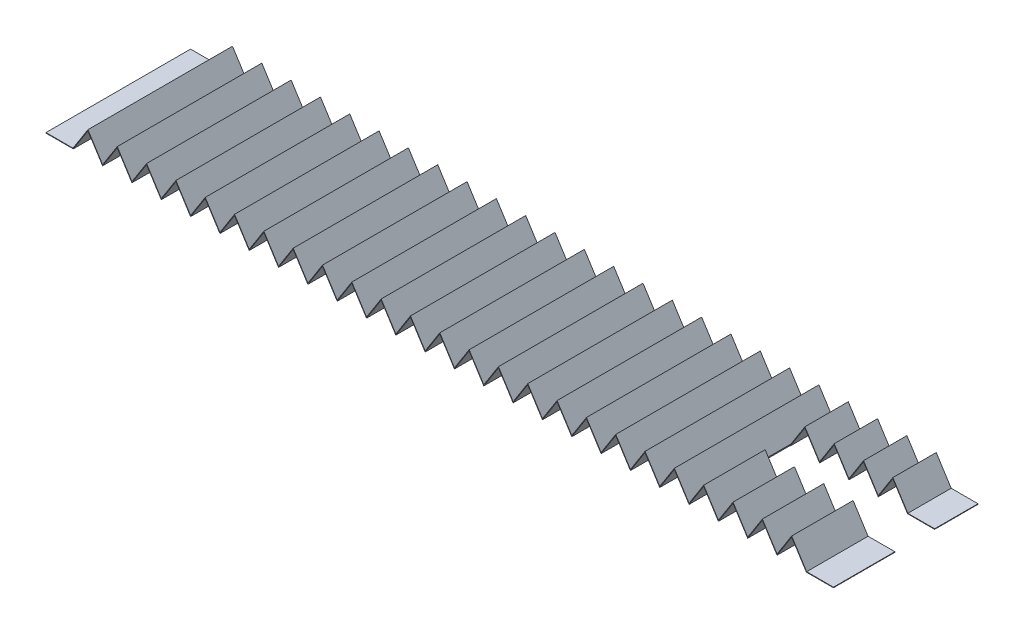
SolidWorks part; units mm, degrees
ref_plane "Front Plane" through (0, 0, 0) normal (0, 0, 1) x (1, 0, 0)
ref_plane "Top Plane" through (0, 0, 0) normal (0, 1, 0) x (1, 0, 0)
ref_plane "Right Plane" through (0, 0, 0) normal (1, 0, 0) x (0, 0, -1)
sketch "Sketch1" plane through (0, 0, 0) normal (0, 0, 1) x (1, 0, 0)
  line L0 (0, 0) -> (8.1143, 12.7345)
  line L1 (8.1143, 12.7345) -> (16.2286, 0)
  line L2 (0, 0) -> (511, 0) construction
  line L3 (16.2286, 0) -> (24.3429, 12.7345)
  line L4 (24.3429, 12.7345) -> (32.4572, 0)
  line L5 (32.4572, 0) -> (40.5715, 12.7345)
  line L6 (40.5715, 12.7345) -> (48.6858, 0)
  line L7 (48.6858, 0) -> (56.8001, 12.7345)
  line L8 (56.8001, 12.7345) -> (64.9144, 0)
  line L9 (64.9144, 0) -> (73.0287, 12.7345)
  line L10 (73.0287, 12.7345) -> (81.143, 0)
  line L11 (81.143, 0) -> (89.2573, 12.7345)
  line L12 (89.2573, 12.7345) -> (97.3716, 0)
  line L13 (97.3716, 0) -> (105.4859, 12.7345)
  line L14 (105.4859, 12.7345) -> (113.6002, 0)
  line L15 (113.6002, 0) -> (121.7145, 12.7345)
  line L16 (121.7145, 12.7345) -> (129.8288, 0)
  line L17 (129.8288, 0) -> (137.9431, 12.7345)
  line L18 (137.9431, 12.7345) -> (146.0574, 0)
  line L19 (0, 0) -> (-15.1, 0)
  line L20 (146.0574, 0) -> (154.1717, 12.7345)
  line L21 (154.1717, 12.7345) -> (162.286, 0)
  line L22 (162.286, 0) -> (170.4003, 12.7345)
  line L23 (170.4003, 12.7345) -> (178.5146, 0)
  line L24 (178.5146, 0) -> (186.6289, 12.7345)
  line L25 (186.6289, 12.7345) -> (194.7432, 0)
  line L26 (194.7432, 0) -> (202.8575, 12.7345)
  line L27 (202.8575, 12.7345) -> (210.9718, 0)
  line L28 (210.9718, 0) -> (219.0861, 12.7345)
  line L29 (219.0861, 12.7345) -> (227.2004, 0)
  line L30 (227.2004, 0) -> (235.3147, 12.7345)
  line L31 (235.3147, 12.7345) -> (243.429, 0)
  line L32 (243.429, 0) -> (251.5433, 12.7345)
  line L33 (251.5433, 12.7345) -> (259.6576, 0)
  line L34 (259.6576, 0) -> (267.7719, 12.7345)
  line L35 (267.7719, 12.7345) -> (275.8862, 0)
  line L36 (275.8862, 0) -> (284.0005, 12.7345)
  line L37 (284.0005, 12.7345) -> (292.1148, 0)
  line L39 (292.1148, 0) -> (300.2291, 12.7345)
  line L40 (300.2291, 12.7345) -> (308.3434, 0)
  line L41 (308.3434, 0) -> (316.4577, 12.7345)
  line L42 (316.4577, 12.7345) -> (324.572, 0)
  line L43 (324.572, 0) -> (332.6863, 12.7345)
  line L44 (332.6863, 12.7345) -> (340.8006, 0)
  line L45 (340.8006, 0) -> (348.9149, 12.7345)
  line L46 (348.9149, 12.7345) -> (357.0292, 0)
  line L47 (357.0292, 0) -> (365.1435, 12.7345)
  line L48 (365.1435, 12.7345) -> (373.2578, 0)
  line L49 (373.2578, 0) -> (381.3721, 12.7345)
  line L50 (340.715, -119) -> (340.715, 187) construction
  line L51 (381.3721, 12.7345) -> (389.4864, 0)
  line L52 (389.4864, 0) -> (397.6007, 12.7345)
  line L53 (397.6007, 12.7345) -> (405.715, 0)
  line L54 (405.715, 0) -> (420.715, 0)
  dimension "D1" = 511
  dimension "D2" = 15.1
  dimension "D3" = 15
  dimension "D4" = 16.2286
  dimension "D6" = 80
  dimension "D5" = 25
extrude "Extrude-Thin1" add sketch "Sketch1" along normal mid plane 80 thin thin type one direction reverse wall 0.3
sketch "Sketch2" plane through (0, 0, 0) normal (0, 1, 0) x (1, 0, 0)
  line L1 (340.715, -6) -> (420.715, -6)
  line L2 (340.715, -6) -> (340.715, 16)
  line L3 (340.715, 16) -> (420.715, 16)
  line L4 (420.715, -6) -> (420.715, 16)
  line L5 (340.715, -6) -> (420.715, 16) construction
  line L6 (340.715, 16) -> (420.715, -6) construction
  line L8 (420.715, -40) -> (420.715, 40) construction
  point P0 (380.715, 5)
  dimension "D1" = 80
  dimension "D2" = 22
  dimension "D3" = 5
extrude "Cut-Extrude4" cut sketch "Sketch2" against normal through all and the other way through all contours L1 L4 L3 L2
